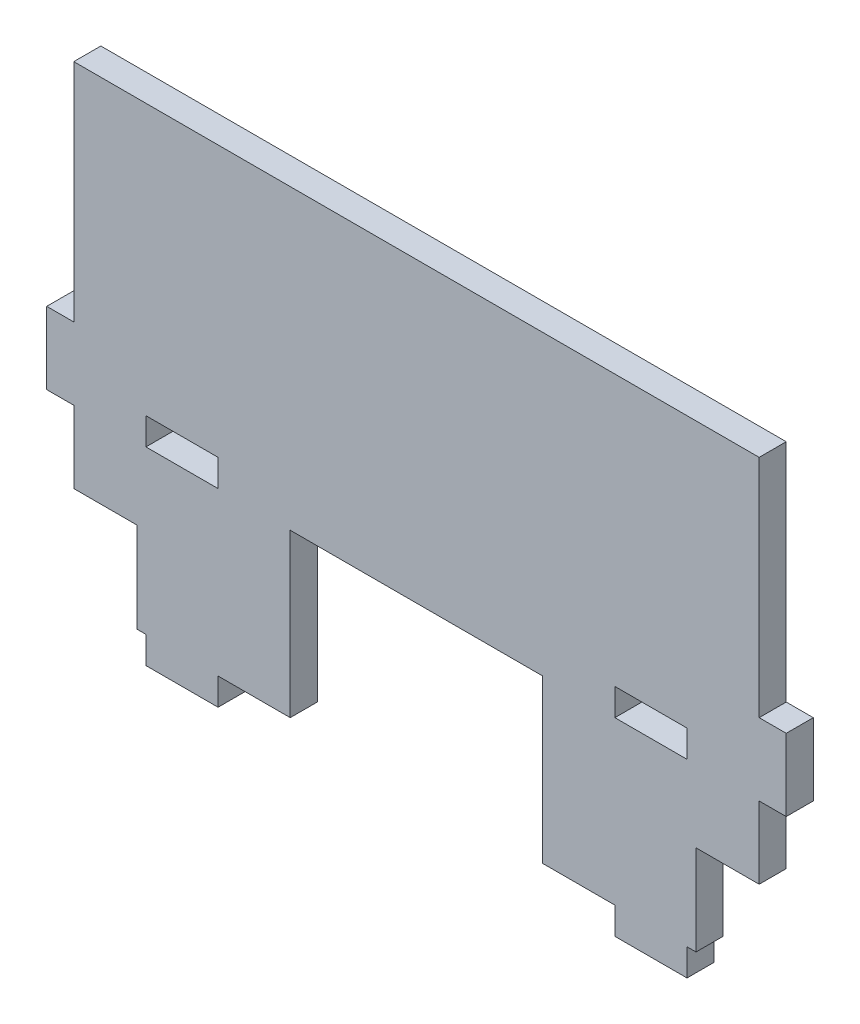
SolidWorks part; units mm, degrees
ref_plane "前视" through (0, 0, 0) normal (0, 0, 1) x (1, 0, 0)
ref_plane "上视" through (0, 0, 0) normal (0, 1, 0) x (1, 0, 0)
ref_plane "右视" through (0, 0, 0) normal (1, 0, 0) x (0, 0, -1)
sketch "草图1" plane through (0, 0, 0) normal (0, 0, 1) x (1, 0, 0)
  line L0 (0, 114.4324) -> (0, -89.0454) construction
  line L1 (38, 0) -> (-38, 0)
  line L2 (-38, 0) -> (-38, -25)
  line L3 (-38, -25) -> (-41, -25)
  line L4 (-41, -25) -> (-41, -33)
  line L5 (-41, -33) -> (-38, -33)
  line L6 (-38, -33) -> (-38, -41)
  line L7 (-38, -41) -> (-31, -41)
  line L8 (-31, -41) -> (-31, -51)
  line L9 (-31, -51) -> (-30, -51)
  line L10 (-30, -51) -> (-30, -54)
  line L11 (-30, -54) -> (-22, -54)
  line L12 (-22, -54) -> (-22, -51)
  line L13 (-22, -51) -> (-14, -51)
  line L14 (-14, -51) -> (-14, -33)
  line L15 (-14, -33) -> (14, -33)
  line L16 (22, -33) -> (22, -30)
  line L17 (-30, -33) -> (-22, -33)
  line L18 (-30, -33) -> (-30, -30)
  line L19 (-30, -30) -> (-22, -30)
  line L20 (-22, -33) -> (-22, -30)
  line L21 (30, -30) -> (22, -30)
  line L22 (30, -33) -> (30, -30)
  line L23 (30, -33) -> (22, -33)
  line L24 (14, -51) -> (14, -33)
  line L25 (22, -51) -> (14, -51)
  line L26 (22, -54) -> (22, -51)
  line L27 (30, -54) -> (22, -54)
  line L28 (30, -51) -> (30, -54)
  line L29 (31, -51) -> (30, -51)
  line L30 (31, -41) -> (31, -51)
  line L32 (38, -41) -> (31, -41)
  line L33 (38, -33) -> (38, -41)
  line L34 (41, -33) -> (38, -33)
  line L35 (41, -25) -> (41, -33)
  line L36 (38, -25) -> (41, -25)
  line L37 (38, 0) -> (38, -25)
  point P27 (0, -33)
  point P41 (0, 0)
  dimension "D1" = 10
  dimension "D2" = 3
  dimension "D3" = 3
  dimension "D4" = 8
  dimension "D5" = 30
  dimension "D6" = 38
  dimension "D7" = 3
  dimension "D8" = 8
  dimension "D9" = 3
  dimension "D10" = 1
  dimension "D11" = 8
  dimension "D12" = 8
  dimension "D13" = 3
  dimension "D14" = 8
  dimension "D15" = 18
  dimension "D16" = 8
extrude "凸台-拉伸1" add sketch "草图1" along normal blind 3
